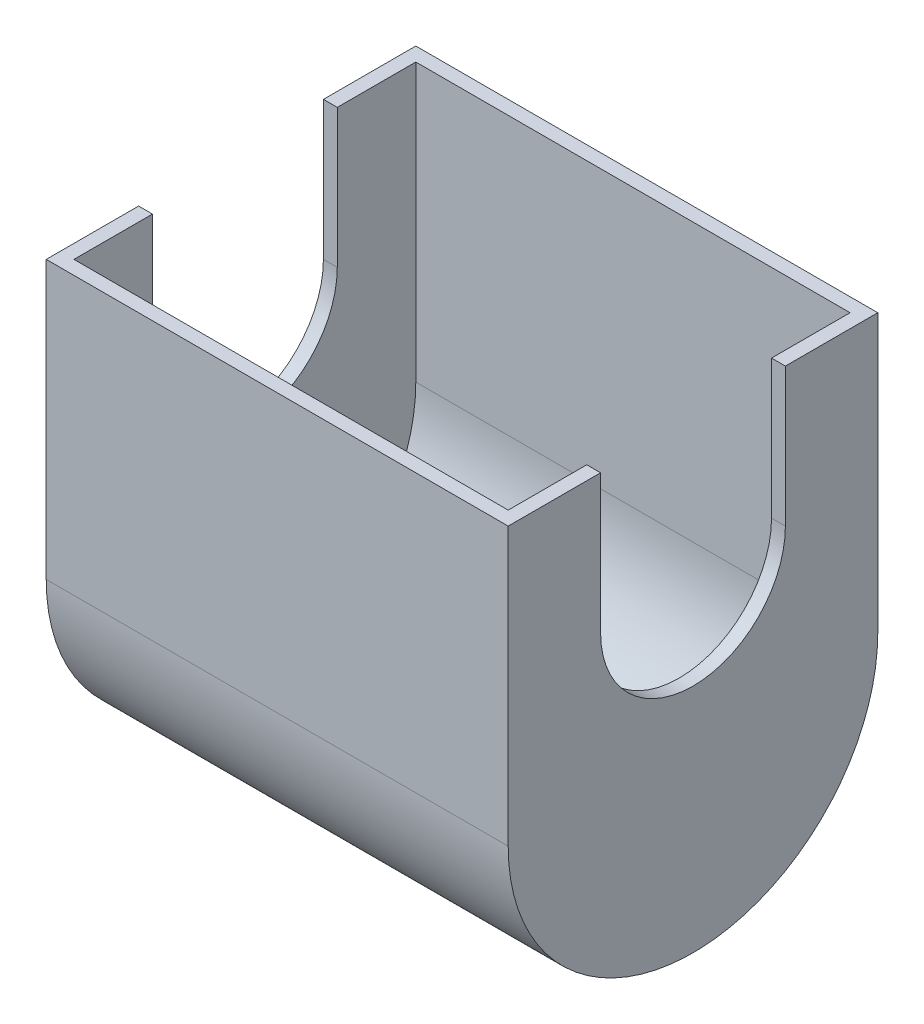
SolidWorks part; units mm, degrees
ref_plane "정면" through (0, 0, 0) normal (0, 0, 1) x (1, 0, 0)
ref_plane "윗면" through (0, 0, 0) normal (0, 1, 0) x (1, 0, 0)
ref_plane "우측면" through (0, 0, 0) normal (1, 0, 0) x (0, 0, -1)
sketch "Sketch1" plane through (0, 0, 0) normal (1, 0, 0) x (0, 0, -1)
  line L0 (0, 0) -> (0, -60) construction
  line L1 (40, 0) -> (40, -60)
  line L2 (-40, 0) -> (-40, -60)
  line L3 (0, 0) -> (0, -30) construction
  line L4 (20, 0) -> (20, -30)
  line L5 (-20, 0) -> (-20, -30)
  line L6 (-40, 0) -> (-20, 0)
  line L7 (20, 0) -> (40, 0)
  arc A1 (-40, -60) -> (40, -60) centre (0, -60) ccw
  arc A3 (-20, -30) -> (20, -30) centre (0, -30) ccw
  point P3 (0, -30)
  point P8 (0, -15)
  dimension "D3" = 60
  dimension "D1" = 40
  dimension "D2" = 80
  dimension "D4" = 30
extrude "Boss-Extrude2" add sketch "Sketch1" along normal blind 100 contours L2 A1 L1 L7 L4 A3 L5 L6
shell "Shell1" thickness 3
